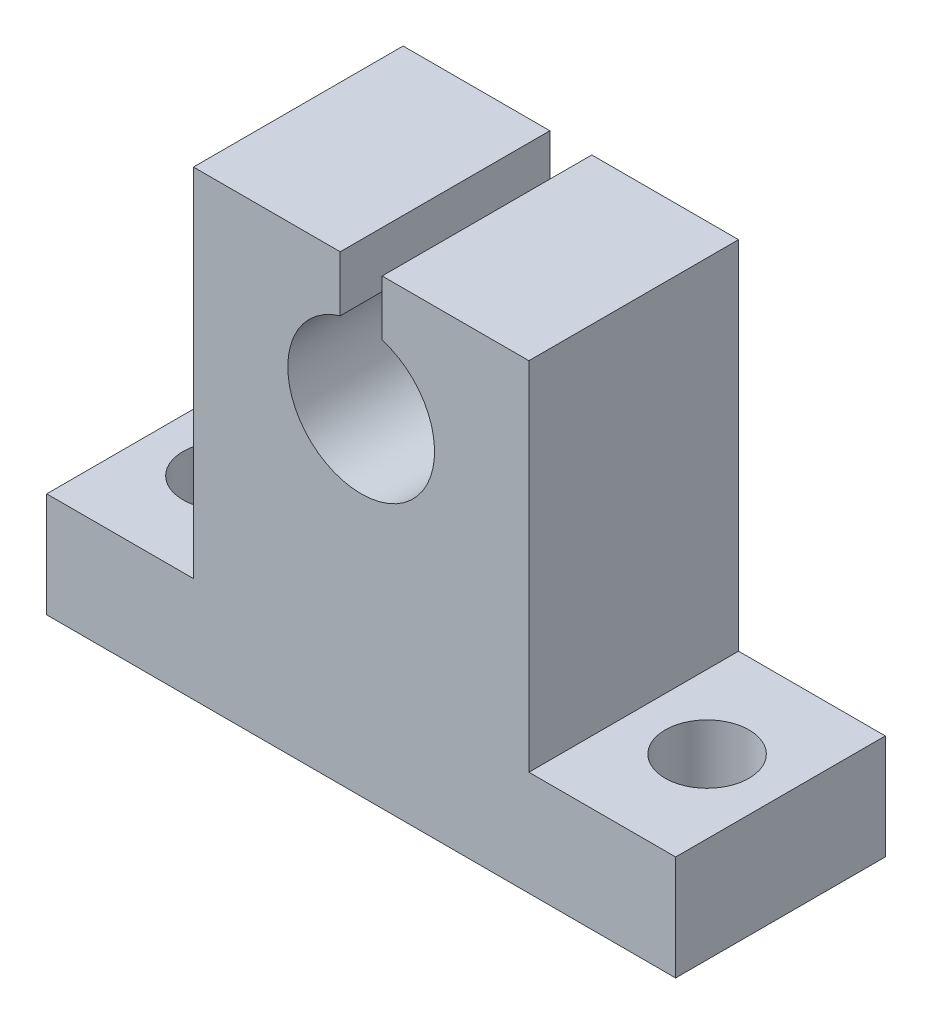
SolidWorks part; units mm, degrees
ref_plane "Plan de face" through (0, 0, 0) normal (0, 0, 1) x (1, 0, 0)
ref_plane "Plan de dessus" through (0, 0, 0) normal (0, 1, 0) x (1, 0, 0)
ref_plane "Plan de droite" through (0, 0, 0) normal (1, 0, 0) x (0, 0, -1)
sketch "Esquisse3" plane through (0, 0, 0) normal (0, 0, 1) x (1, 0, 0)
  line L0 (-15, 0) -> (15, 0)
  line L1 (15, 0) -> (15, 5)
  line L2 (15, 5) -> (8, 5)
  line L3 (8, 5) -> (8, 22)
  line L4 (8, 22) -> (1, 22)
  line L5 (-8, 22) -> (-8, 5)
  line L6 (-8, 5) -> (-15, 5)
  line L7 (-15, 5) -> (-15, 0)
  line L9 (-1, 22) -> (-1, 19.3541)
  line L10 (1, 22) -> (1, 19.3541)
  line L11 (-1, 22) -> (-8, 22)
  arc A0 (-1, 19.3541) -> (1, 19.3541) centre (0, 16) ccw
  point P3 (0, 0)
  dimension "D4" = 7
  dimension "D10" = 16
  dimension "D1" = 30
  dimension "D2" = 5
  dimension "D3" = 5
  dimension "D5" = 7
  dimension "D6" = 7
  dimension "D7" = 16
  dimension "D8" = 17
  dimension "D9" = 2
extrude "Boss.-Extru.1" add sketch "Esquisse3" along normal blind 10
sketch "Esquisse4" plane through (0, 5, 0) normal (0, 1, 0) x (1, 0, 0)
  line L0 (15, -10) -> (15, 0) construction
  line L1 (15, -10) -> (8, -10) construction
  line L2 (0, -13.1327) -> (0, 6.4968) construction
  circle A0 centre (11.5, -5) radius 2
  circle A1 centre (-11.5, -5) radius 2
  point P4 (15, -5)
  point P7 (11.5, -10)
  dimension "D1" = 4
extrude "Enlèv. mat.-Extru.1" cut sketch "Esquisse4" against normal through all
